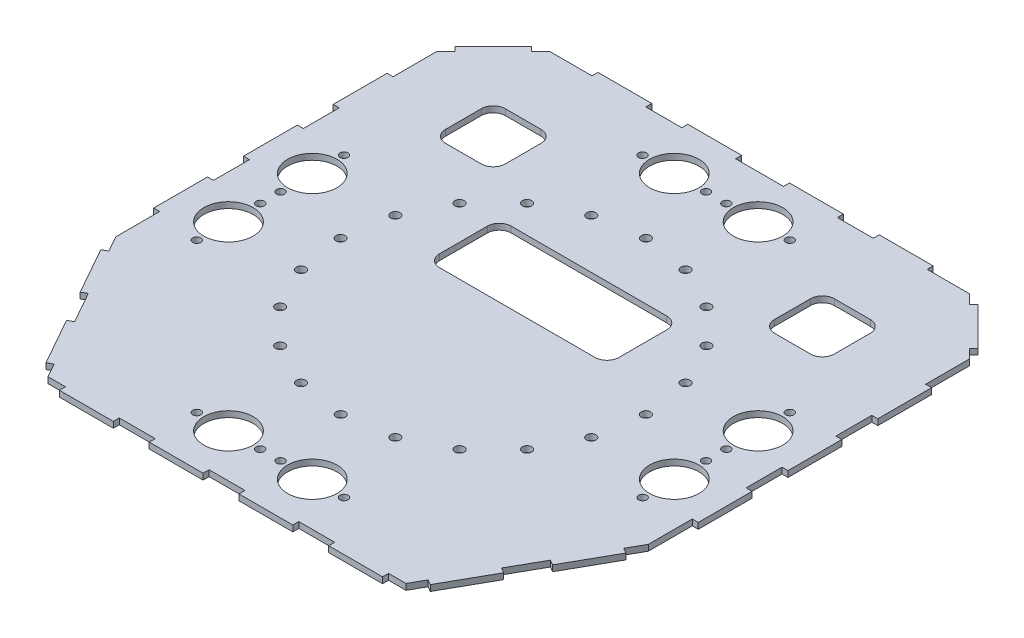
SolidWorks part; units mm, degrees
ref_plane "Plan de face" through (0, 0, 0) normal (0, 0, 1) x (1, 0, 0)
ref_plane "Plan de dessus" through (0, 0, 0) normal (0, 1, 0) x (1, 0, 0)
ref_plane "Plan de droite" through (0, 0, 0) normal (1, 0, 0) x (0, 0, -1)
sketch "Esquisse1" plane through (0, 0, 0) normal (0, 1, 0) x (1, 0, 0)
  line L0 (0, 0) -> (-255, 0) construction
  line L1 (0, 0) -> (-242.5194, 78.7993) construction
  line L2 (0, 405.8971) -> (0, -405.8971) construction
  line L3 (372.4795, 17) -> (372.4795, -17) construction
  line L4 (188.4672, -455) -> (455, -188.4672) construction
  line L5 (455, -188.4672) -> (455, 188.4672)
  line L6 (455, 188.4672) -> (188.4672, 455) construction
  line L7 (188.4672, 455) -> (-188.4672, 455)
  line L8 (-188.4672, 455) -> (-455, 188.4672) construction
  line L9 (-372.4795, 17) -> (-372.4795, -17) construction
  line L10 (70, 372.4795) -> (0, 372.4795) construction
  line L11 (111.25, 372.4795) -> (123, 372.4795) construction
  line L12 (-455, 188.4672) -> (-455, -188.4672)
  line L13 (-455, -188.4672) -> (-188.4672, -455) construction
  line L14 (-188.4672, -455) -> (188.4672, -455)
  line L15 (-150, 160) -> (150, 160)
  line L16 (-150, 160) -> (-150, 40)
  line L17 (-150, 40) -> (150, 40)
  line L18 (150, 160) -> (150, 40)
  line L19 (-372.4795, 0) -> (372.4795, 0) construction
  line L20 (-188.4672, 455) -> (-455, 455)
  line L21 (-455, 455) -> (-455, 188.4672)
  line L22 (188.4672, 455) -> (455, 455)
  line L23 (455, 455) -> (455, 188.4672)
  line L24 (-455, -188.4672) -> (-455, -455) construction
  line L25 (-455, -455) -> (-188.4672, -455) construction
  line L26 (455, -188.4672) -> (455, -455) construction
  line L27 (455, -455) -> (188.4672, -455) construction
  line L28 (-455, -188.4672) -> (-305, -455)
  line L29 (188.4672, -455) -> (305, -455)
  line L30 (305, -455) -> (455, -188.4672)
  line L31 (305, -455) -> (305, -533.2186) construction
  line L32 (305, -533.2186) -> (-305, -533.2186) construction
  line L33 (-305, -533.2186) -> (-305, -455) construction
  line L34 (-305, -455) -> (-188.4672, -455)
  line L35 (0, -533.2186) -> (0, -455) construction
  circle A0 centre (0, 0) radius 239.5 construction
  circle A2 centre (-255, 0) radius 7.75
  circle A3 centre (-242.5194, 78.7993) radius 7.75
  circle A4 centre (-206.2993, 149.8852) radius 7.75
  circle A5 centre (-149.8852, 206.2993) radius 7.75
  circle A6 centre (-78.7993, 242.5194) radius 7.75
  circle A7 centre (0, 255) radius 7.75
  circle A8 centre (78.7993, 242.5194) radius 7.75
  circle A9 centre (149.8852, 206.2993) radius 7.75
  circle A10 centre (206.2993, 149.8852) radius 7.75
  circle A11 centre (242.5194, 78.7993) radius 7.75
  circle A12 centre (255, 0) radius 7.75
  circle A13 centre (242.5194, -78.7993) radius 7.75
  circle A14 centre (206.2993, -149.8852) radius 7.75
  circle A15 centre (149.8852, -206.2993) radius 7.75
  circle A16 centre (78.7993, -242.5194) radius 7.75
  circle A17 centre (0, -255) radius 7.75
  circle A18 centre (-78.7993, -242.5194) radius 7.75
  circle A19 centre (-149.8852, -206.2993) radius 7.75
  circle A20 centre (-206.2993, -149.8852) radius 7.75
  circle A21 centre (-242.5194, -78.7993) radius 7.75
  circle A32 centre (0, 0) radius 255 construction
  circle A34 centre (0, 0) radius 455 construction
  circle A35 centre (0, 0) radius 327 construction
  circle A36 centre (70, 372.4795) radius 52 construction
  circle A37 centre (70, 372.4795) radius 41.25
  circle A38 centre (123, 372.4795) radius 6.75
  circle A39 centre (17, 372.4795) radius 6.75
  circle A40 centre (-17, 372.4795) radius 6.75
  circle A41 centre (-123, 372.4795) radius 6.75
  circle A42 centre (-70, 372.4795) radius 41.25
  circle A43 centre (372.4795, 70) radius 41.25
  circle A44 centre (372.4795, 17) radius 6.75
  circle A45 centre (372.4795, 123) radius 6.75
  circle A46 centre (372.4795, -70) radius 41.25
  circle A47 centre (372.4795, -123) radius 6.75
  circle A48 centre (372.4795, -17) radius 6.75
  circle A49 centre (70, -372.4795) radius 41.25
  circle A50 centre (17, -372.4795) radius 6.75
  circle A51 centre (123, -372.4795) radius 6.75
  circle A52 centre (-70, -372.4795) radius 41.25
  circle A53 centre (-123, -372.4795) radius 6.75
  circle A54 centre (-17, -372.4795) radius 6.75
  circle A55 centre (-372.4795, -70) radius 41.25
  circle A56 centre (-372.4795, -17) radius 6.75
  circle A57 centre (-372.4795, -123) radius 6.75
  circle A58 centre (-372.4795, 70) radius 41.25
  circle A59 centre (-372.4795, 123) radius 6.75
  circle A60 centre (-372.4795, 17) radius 6.75
  circle A61 centre (0, 0) radius 379 construction
  point P67 (0, 0)
  point P68 (0, -455)
  point P131 (0, 0)
  point P139 (0, 160)
  dimension "D2" = 479
  dimension "D3" = 15.5
  dimension "D6" = 910
  dimension "D7" = 654
  dimension "D8" = 104
  dimension "D9" = 82.5
  dimension "D10" = 13.5
  dimension "D11" = 13.5
  dimension "D4" = 255
  dimension "D12" = 53
  dimension "D13" = 106
  dimension "D14" = 70
  dimension "D16" = 300
  dimension "D17" = 120
  dimension "D18" = 40
  dimension "D19" = 150
  dimension "D5" = 20
  dimension "D15" = 4
extrude "Boss.-Extru.1" add sketch "Esquisse1" along normal blind 10
sketch "Esquisse2" plane through (0, 10, 0) normal (0, 1, 0) x (1, 0, 0)
  line L0 (0, 325) -> (-225, 325) construction
  line L1 (-325, 325) -> (-225, 325)
  line L2 (-325, 325) -> (-325, 225)
  line L3 (-325, 225) -> (-225, 225)
  line L4 (-225, 325) -> (-225, 225)
  line L5 (-325, 325) -> (-455, 325) construction
  line L6 (-455, 455) -> (-455, -188.4672) construction
  line L7 (-325, 225) -> (-455, 225) construction
  line L8 (-225, 225) -> (0, 225) construction
  line L9 (0, 325) -> (0, 455) construction
  line L10 (455, 455) -> (-455, 455) construction
  line L11 (0, 325) -> (0, 225) construction
  line L12 (325, 325) -> (325, 225)
  line L13 (325, 325) -> (225, 325)
  line L14 (225, 325) -> (225, 225)
  line L15 (325, 225) -> (225, 225)
  circle A0 centre (0, 0) radius 327 construction
  circle A1 centre (-267.2864, 267.2864) radius 51 construction
  arc A2 (-225, 303.7417) -> (-303.7417, 225) centre (0, 0) ccw construction
  point P20 (-267.2864, 267.2864)
  dimension "D5" = 654
  dimension "D6" = 102
  dimension "D1" = 130
  dimension "D2" = 130
  dimension "D3" = 100
  dimension "D4" = 100
chamfer "Chanfrein1" distance 100 angle 45 2 edges at (455, 5, -455) (-455, 5, -455)
extrude "Enlèv. mat.-Extru.1" cut sketch "Esquisse2" against normal through all
fillet "Congé1" radius 20 12 edges at (-150, 5, -40) (150, 5, -40) (150, 5, -160) (-150, 5, -160) (-325, 5, -225) (225, 5, -225) (325, 5, -225) (225, 5, -325) (325, 5, -325) (-225, 5, -225) (-225, 5, -325) (-325, 5, -325)
sketch "Esquisse3" plane through (0, 10, 0) normal (0, 1, 0) x (1, 0, 0)
  line L0 (-305, -455) -> (-455, -188.4672) construction
  line L1 (-455, -188.4672) -> (-455, 355) construction
  line L2 (-455, 355) -> (-355, 455) construction
  line L3 (-355, 455) -> (355, 455) construction
  line L4 (355, 455) -> (455, 355) construction
  line L5 (455, 355) -> (455, -188.4672) construction
  line L6 (455, -188.4672) -> (305, -455) construction
  line L7 (305, -455) -> (-305, -455) construction
  line L8 (-445, -185.8465) -> (-445, 350.8579) construction
  line L9 (-445, 350.8579) -> (-350.8579, 445) construction
  line L10 (-350.8579, 445) -> (350.8579, 445) construction
  line L11 (350.8579, 445) -> (445, 350.8579) construction
  line L12 (445, 350.8579) -> (445, -185.8465) construction
  line L13 (445, -185.8465) -> (299.153, -445) construction
  line L14 (299.153, -445) -> (-299.153, -445) construction
  line L15 (-299.153, -445) -> (-445, -185.8465) construction
  line L16 (0, -455) -> (0, 455) construction
  line L17 (30, -445) -> (-30, -445)
  line L18 (-30, -445) -> (-30, -455)
  line L19 (-30, -455) -> (-120, -455)
  line L20 (-120, -455) -> (-120, -445)
  line L21 (-120, -445) -> (-180, -445)
  line L22 (-299.153, -445) -> (-312.4315, -421.4055)
  line L23 (-312.4315, -421.4055) -> (-321.1462, -426.31)
  line L24 (-321.1462, -426.31) -> (-365.2866, -347.8777)
  line L25 (-365.2866, -347.8777) -> (-356.5719, -342.9732)
  line L26 (-356.5719, -342.9732) -> (-385.9987, -290.685)
  line L27 (-385.9987, -290.685) -> (-394.7134, -295.5895)
  line L28 (-394.7134, -295.5895) -> (-438.8538, -217.1571)
  line L29 (-438.8538, -217.1571) -> (-430.1391, -212.2527)
  line L30 (-430.1391, -212.2527) -> (-445, -185.8465)
  line L31 (-180, -445) -> (-180, -455)
  line L32 (-180, -455) -> (-270, -455)
  line L33 (-455, -188.4672) -> (-305, -455) construction
  line L34 (-270, -455) -> (-270, -445)
  line L35 (-445, -185.8465) -> (-445, -112.4943)
  line L36 (-445, -112.4943) -> (-455, -112.4943)
  line L37 (-455, -112.4943) -> (-455, -22.4943)
  line L38 (-455, -22.4943) -> (-445, -22.4943)
  line L39 (-445, -22.4943) -> (-445, 37.5057)
  line L40 (-445, 187.5057) -> (-455, 187.5057)
  line L41 (-455, 277.5057) -> (-455, 187.5057)
  line L42 (-455, 37.5057) -> (-445, 37.5057)
  line L43 (-445, 127.5057) -> (-445, 187.5057)
  line L44 (-445, 127.5057) -> (-455, 127.5057)
  line L45 (-455, 127.5057) -> (-455, 37.5057)
  line L46 (-455, 277.5057) -> (-445, 277.5057)
  line L47 (-445, 277.5057) -> (-445, 350.8579)
  line L48 (-445, 350.8579) -> (-429.7487, 366.1091)
  line L49 (-429.7487, 366.1091) -> (-436.8198, 373.1802)
  line L50 (-436.8198, 373.1802) -> (-373.1802, 436.8198)
  line L51 (-373.1802, 436.8198) -> (-366.1091, 429.7487)
  line L52 (-366.1091, 429.7487) -> (-350.8579, 445)
  line L53 (-350.8579, 445) -> (-280, 445)
  line L54 (-280, 445) -> (-280, 455)
  line L55 (-280, 455) -> (-190, 455)
  line L56 (-190, 455) -> (-190, 445)
  line L57 (-190, 445) -> (-130, 445)
  line L58 (-130, 445) -> (-130, 455)
  line L59 (-130, 455) -> (-40, 455)
  line L60 (-40, 455) -> (-40, 445)
  line L61 (-40, 445) -> (40, 445)
  line L62 (-455, 355) -> (-455, -188.4672) construction
  line L63 (-305, -455) -> (305, -455) construction
  line L64 (-305, -455) -> (305, -455) construction
  line L65 (-371.2853, -316.8291) -> (-380, -321.7336) construction
  line L66 (-445, 350.8579) -> (-424.4564, 350.8579) construction
  line L67 (-424.4564, 350.8579) -> (-424.4564, -185.8465) construction
  line L68 (-424.4564, -185.8465) -> (-445, -185.8465) construction
  line L69 (-455, 82.5057) -> (-424.4564, 82.5057) construction
  line L70 (-405, 405) -> (-397.9289, 397.9289) construction
  line L71 (-350.8579, 445) -> (-350.8579, 415.2026) construction
  line L72 (-350.8579, 415.2026) -> (0, 415.2026) construction
  line L73 (-270, -445) -> (-299.153, -445)
  line L74 (30, -445) -> (30, -455)
  line L75 (30, -455) -> (120, -455)
  line L76 (120, -455) -> (120, -445)
  line L77 (270, -445) -> (299.153, -445)
  line L78 (299.153, -445) -> (312.4315, -421.4055)
  line L79 (312.4315, -421.4055) -> (321.1462, -426.31)
  line L80 (321.1462, -426.31) -> (365.2866, -347.8777)
  line L81 (365.2866, -347.8777) -> (356.5719, -342.9732)
  line L82 (356.5719, -342.9732) -> (385.9987, -290.685)
  line L83 (385.9987, -290.685) -> (394.7134, -295.5895)
  line L84 (394.7134, -295.5895) -> (438.8538, -217.1571)
  line L85 (438.8538, -217.1571) -> (430.1391, -212.2527)
  line L86 (430.1391, -212.2527) -> (445, -185.8465)
  line L87 (270, -455) -> (270, -445)
  line L88 (180, -455) -> (270, -455)
  line L89 (120, -445) -> (180, -445)
  line L90 (180, -445) -> (180, -455)
  line L91 (445, -185.8465) -> (445, -112.4943)
  line L92 (445, -112.4943) -> (455, -112.4943)
  line L93 (455, -112.4943) -> (455, -22.4943)
  line L94 (455, -22.4943) -> (445, -22.4943)
  line L95 (445, -22.4943) -> (445, 37.5057)
  line L96 (455, 37.5057) -> (445, 37.5057)
  line L97 (455, 127.5057) -> (455, 37.5057)
  line L98 (445, 127.5057) -> (455, 127.5057)
  line L99 (445, 127.5057) -> (445, 187.5057)
  line L100 (445, 187.5057) -> (455, 187.5057)
  line L101 (455, 277.5057) -> (455, 187.5057)
  line L102 (455, 277.5057) -> (445, 277.5057)
  line L103 (445, 277.5057) -> (445, 350.8579)
  line L104 (445, 350.8579) -> (429.7487, 366.1091)
  line L105 (429.7487, 366.1091) -> (436.8198, 373.1802)
  line L106 (436.8198, 373.1802) -> (373.1802, 436.8198)
  line L107 (373.1802, 436.8198) -> (366.1091, 429.7487)
  line L108 (366.1091, 429.7487) -> (350.8579, 445)
  line L109 (350.8579, 445) -> (280, 445)
  line L110 (280, 445) -> (280, 455)
  line L111 (280, 455) -> (190, 455)
  line L112 (190, 455) -> (190, 445)
  line L113 (190, 445) -> (130, 445)
  line L114 (130, 445) -> (130, 455)
  line L115 (130, 455) -> (40, 455)
  line L116 (40, 455) -> (40, 445)
  line L118 (-713.9976, 598.4866) -> (783.8122, 598.4866)
  line L119 (-713.9976, 598.4866) -> (-713.9976, -681.5644)
  line L120 (-713.9976, -681.5644) -> (783.8122, -681.5644)
  line L121 (783.8122, 598.4866) -> (783.8122, -681.5644)
  point P85 (0, -445)
  point P97 (180, -445)
  point P124 (0, 445)
  dimension "D2" = 30
  dimension "D3" = 90
  dimension "D4" = 60
  dimension "D5" = 90
  dimension "D6" = 90
  dimension "D7" = 90
  dimension "D8" = 60
  dimension "D9" = 90
  dimension "D10" = 60
  dimension "D11" = 90
  dimension "D12" = 60
  dimension "D13" = 90
  dimension "D14" = 90
  dimension "D15" = 90
  dimension "D16" = 90
  dimension "D17" = 60
  dimension "D18" = 40
  dimension "D1" = 10
extrude "Enlèv. mat.-Extru.2" cut sketch "Esquisse3" against normal through all
